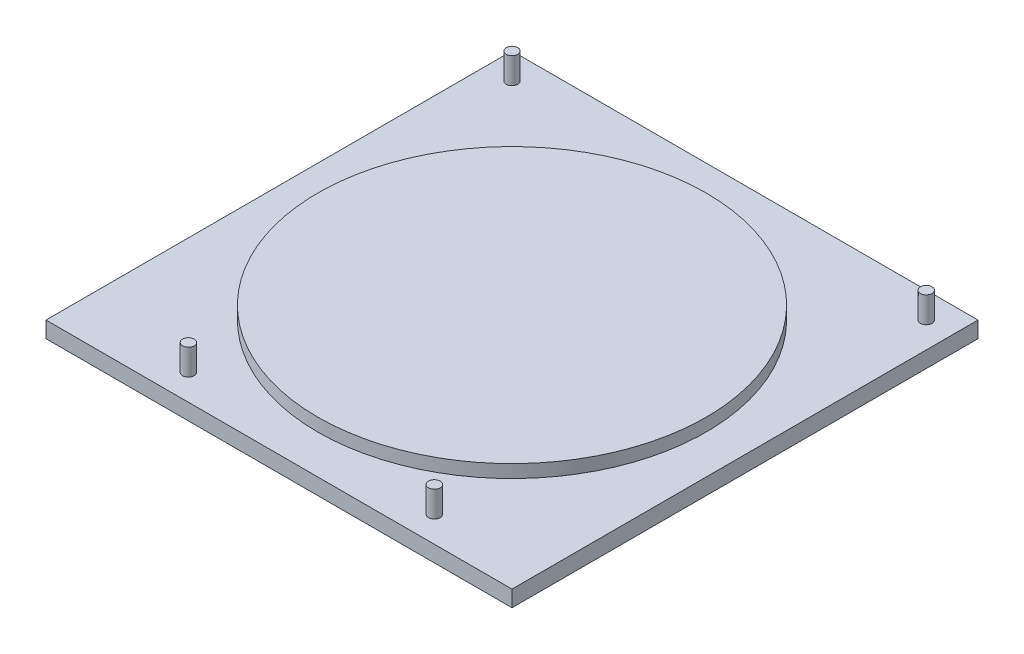
SolidWorks part; units mm, degrees
ref_plane "Front Plane" through (0, 0, 0) normal (0, 0, 1) x (1, 0, 0)
ref_plane "Top Plane" through (0, 0, 0) normal (0, 1, 0) x (1, 0, 0)
ref_plane "Right Plane" through (0, 0, 0) normal (1, 0, 0) x (0, 0, -1)
sketch "Sketch1" plane through (0, 0, 0) normal (0, 1, 0) x (1, 0, 0)
  line L1 (-13.5565, 42.929) -> (77.8835, 42.929)
  line L2 (-13.5565, 42.929) -> (-13.5565, -48.511)
  line L3 (-13.5565, -48.511) -> (77.8835, -48.511)
  line L4 (77.8835, 42.929) -> (77.8835, -48.511)
  dimension "D1" = 91.44
  dimension "D2" = 91.44
extrude "Boss-Extrude1" add sketch "Sketch1" along normal blind 3.175
sketch "Sketch2" plane through (0, 3.175, 0) normal (0, 1, 0) x (1, 0, 0)
  circle A0 centre (32.1635, -2.791) radius 38.1
  dimension "D1" = 76.2
extrude "Boss-Extrude2" add sketch "Sketch2" along normal blind 2.54
sketch "Sketch4" plane through (0, 3.175, 0) normal (0, 1, 0) x (1, 0, 0)
  circle A0 centre (9.3035, -43.431) radius 1.143
  circle A1 centre (57.5635, -43.431) radius 1.143
  dimension "D1" = 2.286
  dimension "D2" = 2.286
extrude "Boss-Extrude4" add sketch "Sketch4" along normal blind 5.08
sketch "Sketch5" plane through (0, 3.175, 0) normal (0, 1, 0) x (1, 0, 0)
  circle A0 centre (-8.4765, 37.849) radius 1.143
  circle A1 centre (72.8035, 37.849) radius 1.143
  dimension "D5" = 2.286
  dimension "D6" = 2.286
extrude "Boss-Extrude5" add sketch "Sketch5" along normal blind 5.08
